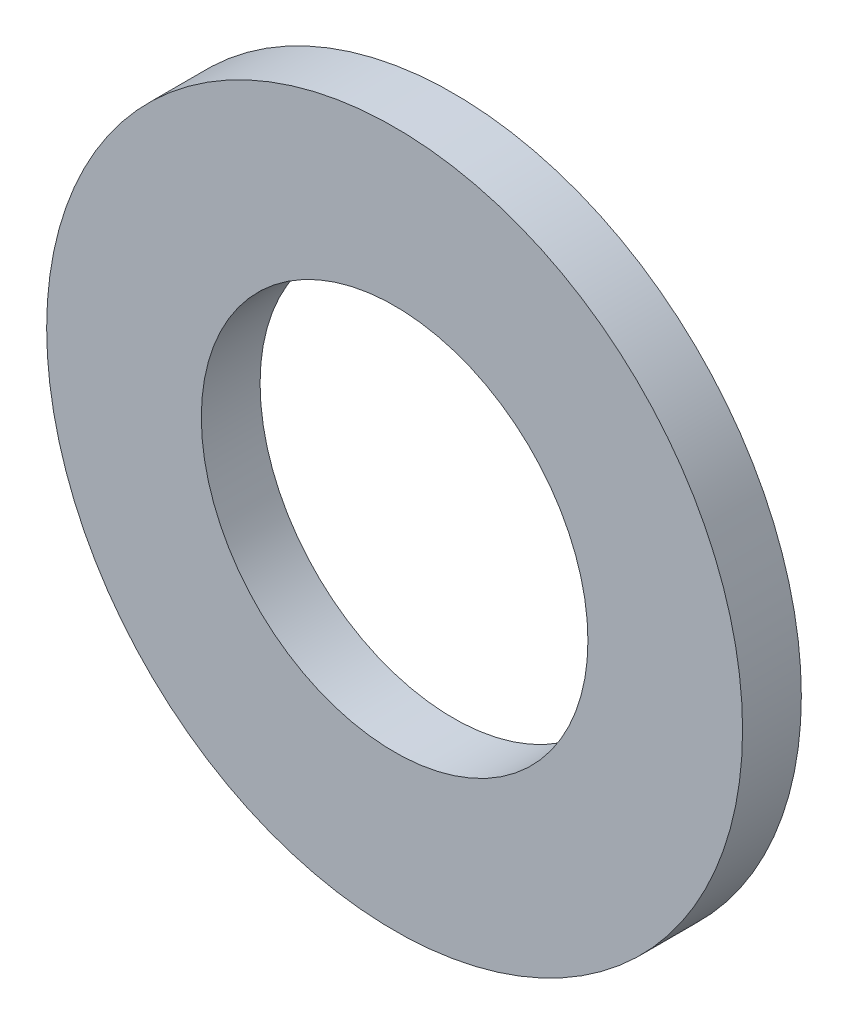
SolidWorks part; units mm, degrees
material "Alloy Steel"
ref_plane "Front Plane" through (0, 0, 0) normal (0, 0, 1) x (1, 0, 0)
ref_plane "Top Plane" through (0, 0, 0) normal (0, 1, 0) x (1, 0, 0)
ref_plane "Right Plane" through (0, 0, 0) normal (1, 0, 0) x (0, 0, -1)
sketch "Sketch1" plane through (0, 0, 0) normal (0, 0, 1) x (1, 0, 0)
  line L0 (-7.9375, 0) -> (7.9375, 0) construction
  circle A0 centre (0, 0) radius 14.2875 construction
  circle A1 centre (0, 0) radius 7.9375 construction
  dimension "OD" = 28.575
  dimension "ID" = 15.875
  dimension "For Shaft Diameter" = 15.875
sketch "Sketch2" plane through (0, 0, 0) normal (1, 0, 0) x (0, 0, -1)
  line L4 (1.2065, 14.2875) -> (-1.2065, 14.2875) construction
  point P0 (0, 14.2875)
  dimension "Thickness" = 2.413
sketch "Sketch3" plane through (0, 0, 0) normal (0, 0, 1) x (1, 0, 0)
  circle A0 centre (0, 0) radius 7.9375 construction
  circle A1 centre (0, 0) radius 14.2875 construction
  circle A3 centre (0, 0) radius 7.9375
  circle A5 centre (0, 0) radius 14.2875
extrude "Boss-Extrude1" add sketch "Sketch3" against normal up to vertex (1.2065 mm away) and the other way up to vertex (1.2065 mm away)
equation "\"D1\"= \"Thickness@Sketch2\""
